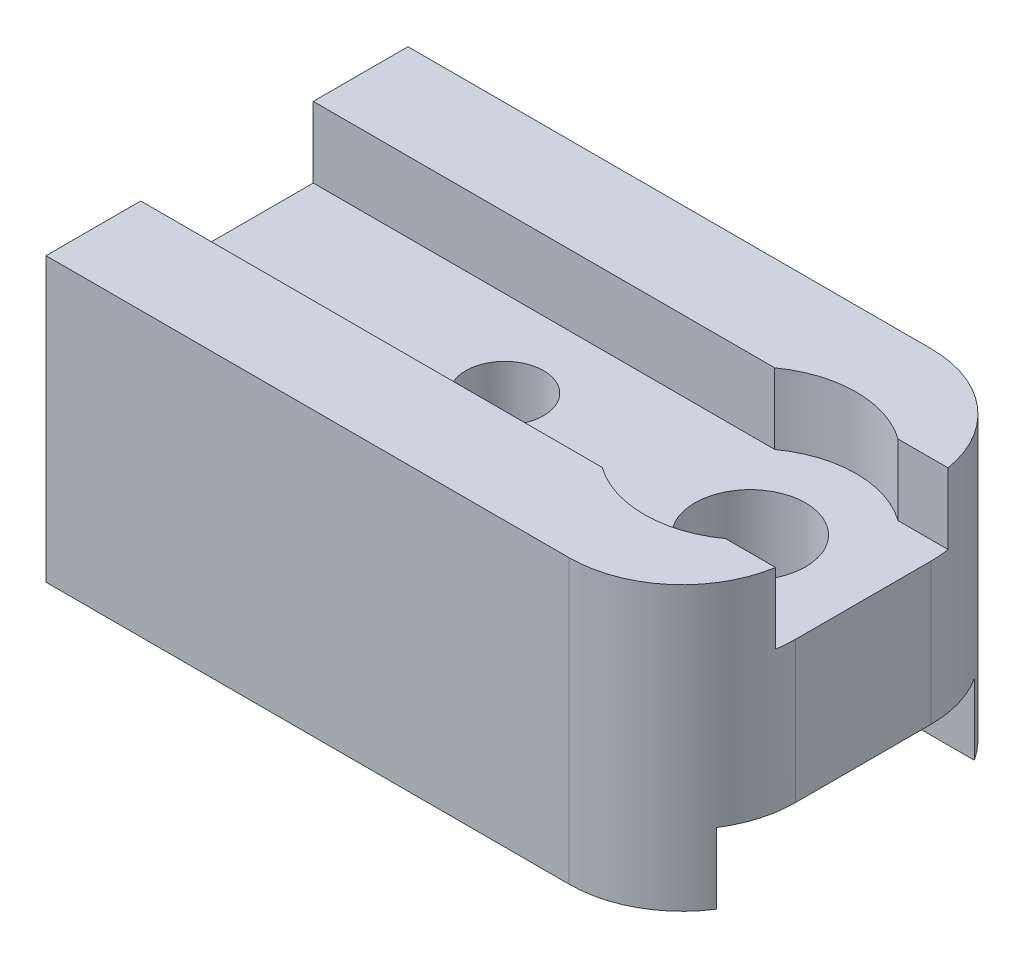
SolidWorks part; units mm, degrees
material "PVC Rigid"
ref_plane "Front Plane" through (0, 0, 0) normal (0, 0, 1) x (1, 0, 0)
ref_plane "Top Plane" through (0, 0, 0) normal (0, 1, 0) x (1, 0, 0)
ref_plane "Right Plane" through (0, 0, 0) normal (1, 0, 0) x (0, 0, -1)
sketch "Sketch1" plane through (0, 0, 0) normal (0, 1, 0) x (1, 0, 0)
  line L1 (0, 0) -> (28.575, 0)
  line L2 (0, 0) -> (0, 16.256)
  line L3 (0, 16.256) -> (28.575, 16.256)
  line L4 (28.575, 0) -> (28.575, 16.256)
  circle A0 centre (23.495, 8.128) radius 2.4892
  circle A1 centre (12.4714, 8.128) radius 1.75
  point P10 (28.575, 8.128)
  dimension "D3" = 3.5
  dimension "D4" = 4.9784
  dimension "D1" = 16.256
  dimension "D2" = 28.575
  dimension "D5" = 11.0236
  dimension "D6" = 5.08
extrude "Boss-Extrude1" add sketch "Sketch1" along normal blind 12.7
sketch "Sketch2" plane through (0, 12.7, 0) normal (0, 1, 0) x (1, 0, 0)
  line L0 (0, 16.256) -> (0, 0) construction
  line L1 (-2.4159, 12.0015) -> (33.9821, 12.0015)
  line L2 (-2.4159, 12.0015) -> (-2.4159, 4.2545)
  line L3 (-2.4159, 4.2545) -> (33.9821, 4.2545)
  line L4 (33.9821, 12.0015) -> (33.9821, 4.2545)
  point P4 (-2.4159, 8.128)
  point P9 (0, 8.128)
  dimension "D1" = 7.747
extrude "Cut-Extrude1" cut sketch "Sketch2" against normal blind 3.175
sketch "Sketch3" plane through (0, 0, 0) normal (0, -1, 0) x (1, 0, 0)
  line L0 (0, -16.256) -> (0, 0) construction
  line L1 (-1.0667, -2.3368) -> (31.9659, -2.3368)
  line L2 (-1.0667, -2.3368) -> (-1.0667, -13.9192)
  line L3 (-1.0667, -13.9192) -> (31.9659, -13.9192)
  line L4 (31.9659, -2.3368) -> (31.9659, -13.9192)
  point P4 (-1.0667, -8.128)
  point P7 (0, -8.128)
  dimension "D1" = 11.5824
extrude "Cut-Extrude2" cut sketch "Sketch3" against normal blind 3.175
sketch "Sketch4" plane through (0, 3.175, 0) normal (0, -1, 0) x (1, 0, 0)
  circle A0 centre (12.4714, -8.128) radius 3.7465
  dimension "D1" = 7.493
extrude "Cut-Extrude3" cut sketch "Sketch4" against normal blind 3.6322
fillet "Fillet1" radius 5.08 2 edges at (28.575, 6.35, -16.256) (28.575, 6.35, 0)
sketch "Sketch5" plane through (0, 9.525, 0) normal (0, 1, 0) x (1, 0, 0)
  circle A0 centre (23.495, 8.128) radius 4.7625
  dimension "D1" = 9.525
extrude "Cut-Extrude4" cut sketch "Sketch5" along normal through all
